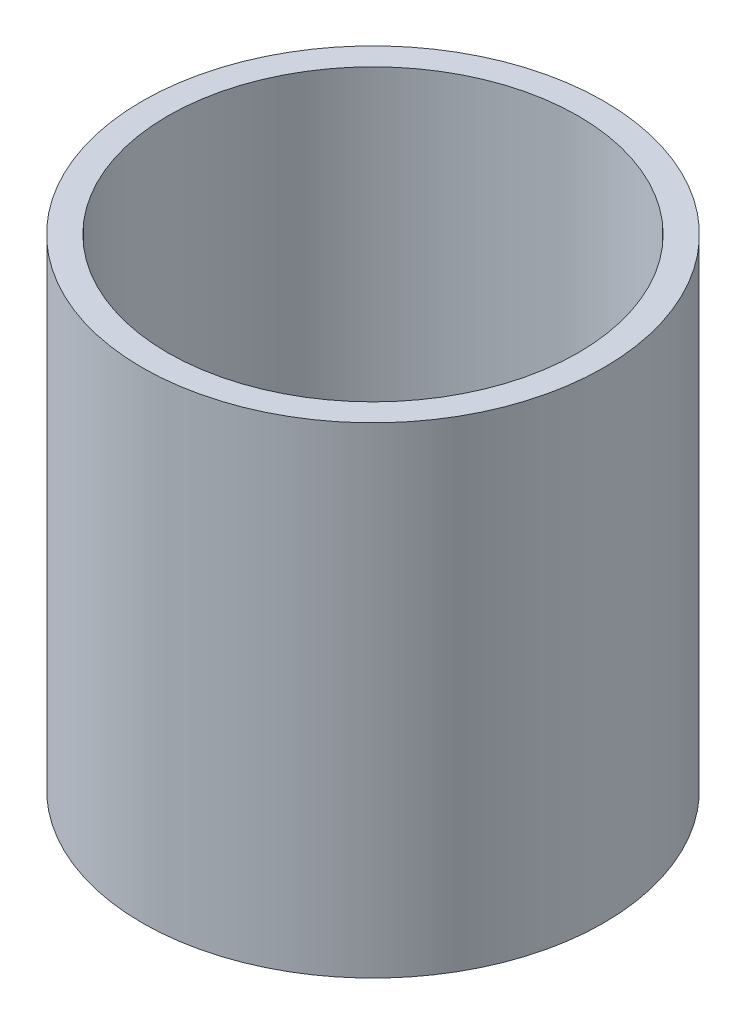
SolidWorks part; units mm, degrees
ref_plane "Front Plane" through (0, 0, 0) normal (0, 0, 1) x (1, 0, 0)
ref_plane "Top Plane" through (0, 0, 0) normal (0, 1, 0) x (1, 0, 0)
ref_plane "Right Plane" through (0, 0, 0) normal (1, 0, 0) x (0, 0, -1)
sketch "Sketch1" plane through (0, 0, 0) normal (0, 1, 0) x (1, 0, 0)
  circle A0 centre (0, 0) radius 4.572
  dimension "D1" = 9.144
extrude "Boss-Extrude1" add sketch "Sketch1" along normal blind 9.525
sketch "Sketch2" plane through (0, 9.525, 0) normal (0, 1, 0) x (1, 0, 0)
  circle A0 centre (0, 0) radius 4.064
  dimension "D1" = 8.128
extrude "Cut-Extrude1" cut sketch "Sketch2" against normal through all
